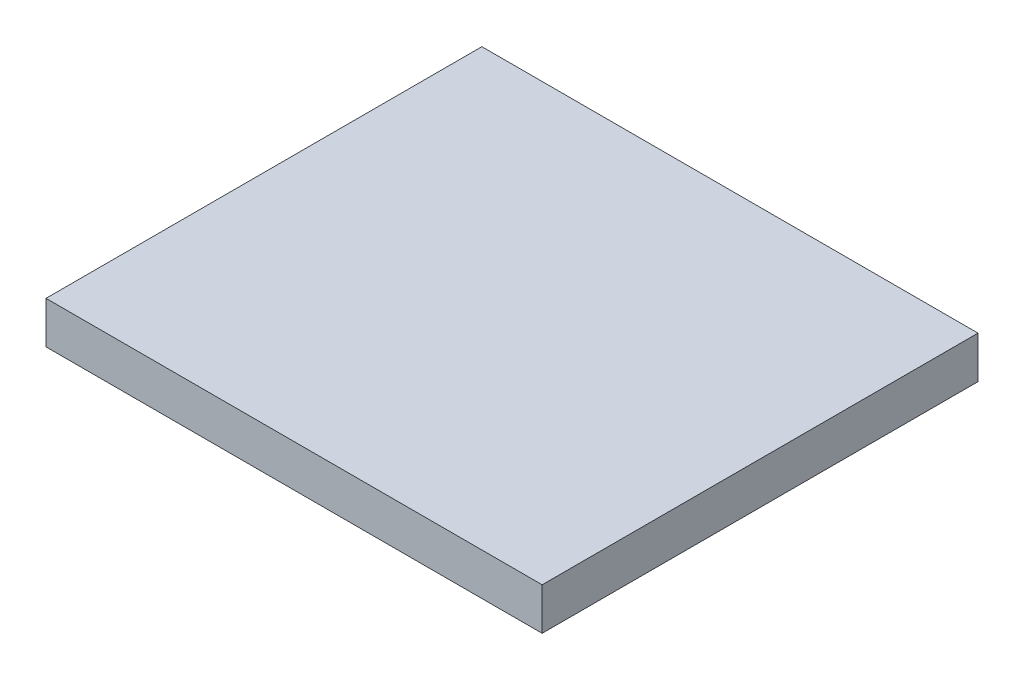
SolidWorks part; units mm, degrees
ref_plane "Front Plane" through (0, 0, 0) normal (0, 0, 1) x (1, 0, 0)
ref_plane "Top Plane" through (0, 0, 0) normal (0, 1, 0) x (1, 0, 0)
ref_plane "Right Plane" through (0, 0, 0) normal (1, 0, 0) x (0, 0, -1)
sketch "Sketch1" plane through (0, 0, 0) normal (0, 1, 0) x (1, 0, 0)
  line L1 (-17.7, -15.55) -> (17.7, -15.55)
  line L2 (-17.7, -15.55) -> (-17.7, 15.55)
  line L3 (-17.7, 15.55) -> (17.7, 15.55)
  line L4 (17.7, -15.55) -> (17.7, 15.55)
  line L5 (-17.7, -15.55) -> (17.7, 15.55) construction
  line L6 (-17.7, 15.55) -> (17.7, -15.55) construction
  point P0 (0, 0)
  dimension "D1" = 35.4
  dimension "D2" = 31.1
extrude "Boss-Extrude2" add sketch "Sketch1" along normal blind 3
